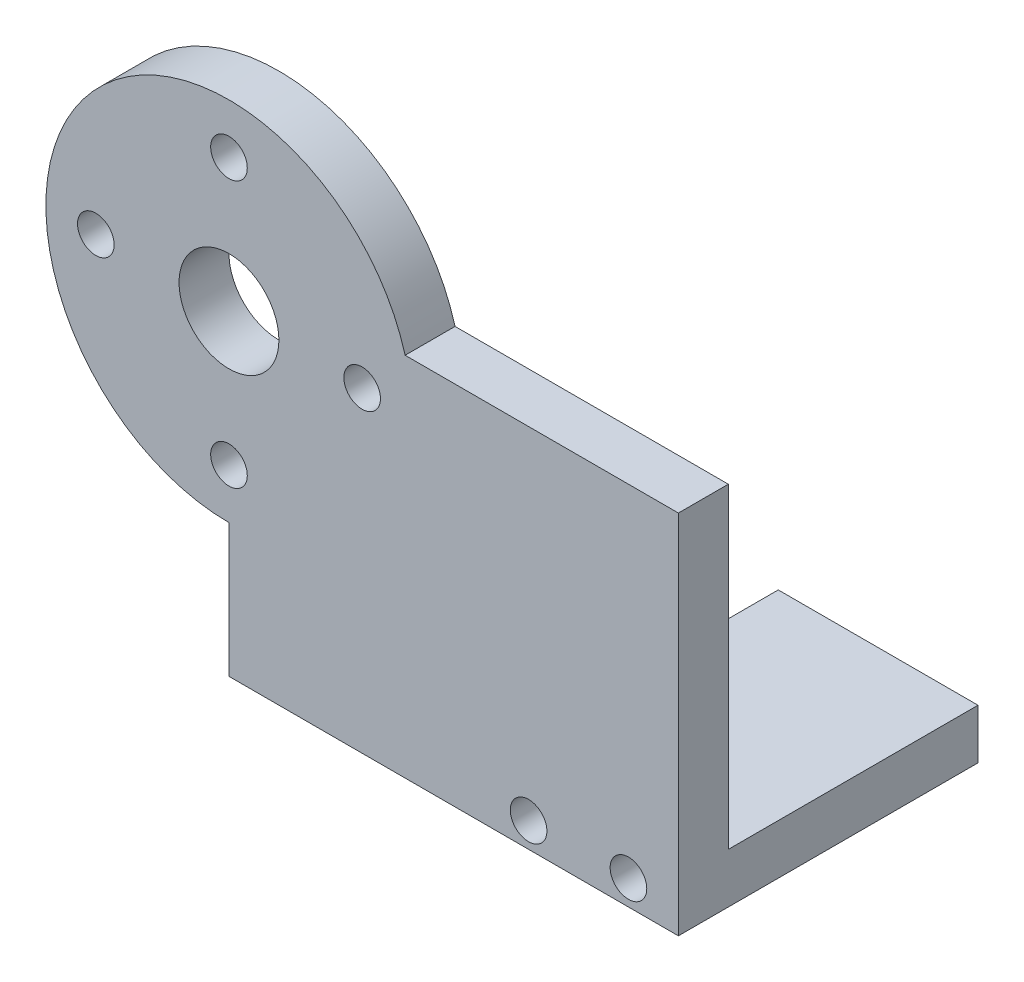
SolidWorks part; units mm, degrees
ref_plane "Front Plane" through (0, 0, 0) normal (0, 0, 1) x (1, 0, 0)
ref_plane "Top Plane" through (0, 0, 0) normal (0, 1, 0) x (1, 0, 0)
ref_plane "Right Plane" through (0, 0, 0) normal (1, 0, 0) x (0, 0, -1)
sketch "Stock_horn_attachment_profile" plane through (0, 0, 0) normal (0, 0, 1) x (1, 0, 0)
  circle A0 centre (0, 0) radius 11
  dimension "D1" = 22
extrude "Stock_horn_attachment" add sketch "Stock_horn_attachment_profile" along normal blind 3 from offset 15
sketch "Finger_arm_profile" plane through (0, 0, 0) normal (0, 0, 1) x (1, 0, 0)
  line L1 (0, -19) -> (27, -19)
  line L2 (0, -19) -> (0, 3)
  line L3 (0, 3) -> (27, 3)
  line L4 (27, -19) -> (27, 3)
  dimension "D1" = 27
  dimension "D2" = 22
extrude "Finger_arm" add sketch "Finger_arm_profile" along normal blind 3 from offset 15
sketch "Descending_contact_finger_profile" plane through (0, 0, 0) normal (0, 0, 1) x (1, 0, 0)
  line L1 (15, -19) -> (27, -19)
  line L2 (15, -19) -> (15, -16)
  line L3 (15, -16) -> (27, -16)
  line L4 (27, -19) -> (27, -16)
  dimension "D1" = 12
  dimension "D2" = 3
extrude "Descending_contact_finger" add sketch "Descending_contact_finger_profile" along normal blind 18
sketch "Horn_center_access_profile" plane through (0, 0, 0) normal (0, 0, 1) x (1, 0, 0)
  circle A0 centre (0, 0) radius 3
  dimension "D1" = 6
extrude "Horn_center_access" cut sketch "Horn_center_access_profile" along normal through all from offset 50
sketch "Horn_screws_profile" plane through (0, 0, 0) normal (0, 0, 1) x (1, 0, 0)
  circle A0 centre (0, -8) radius 1.1
  circle A1 centre (0, 8) radius 1.1
  circle A2 centre (-8, 0) radius 1.1
  circle A3 centre (8, 0) radius 1.1
  dimension "D1" = 2.2
  dimension "D2" = 2.2
  dimension "D3" = 2.2
  dimension "D4" = 2.2
extrude "Horn_screws" cut sketch "Horn_screws_profile" along normal through all from offset 50
sketch "Contact_pad_keeper_profile" plane through (0, 0, 0) normal (0, 0, 1) x (1, 0, 0)
  circle A0 centre (18, -17.5) radius 1.1
  circle A1 centre (24, -17.5) radius 1.1
  dimension "D1" = 2.2
  dimension "D2" = 2.2
extrude "Contact_pad_keeper" cut sketch "Contact_pad_keeper_profile" along normal through all from offset 50
